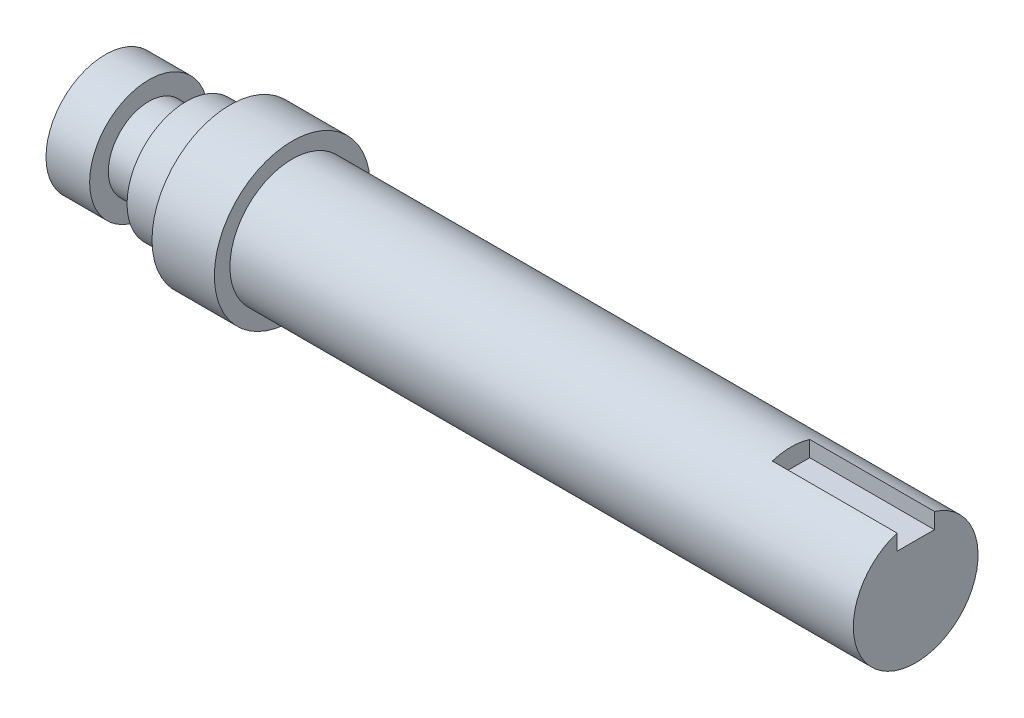
SolidWorks part; units mm, degrees
ref_plane "Front Plane" through (0, 0, 0) normal (0, 0, 1) x (1, 0, 0)
ref_plane "Top Plane" through (0, 0, 0) normal (0, 1, 0) x (1, 0, 0)
ref_plane "Right Plane" through (0, 0, 0) normal (1, 0, 0) x (0, 0, -1)
sketch "Sketch1" plane through (0, 0, 0) normal (0, 0, 1) x (1, 0, 0)
  line L0 (0, 0) -> (0, 10)
  line L1 (0, 10) -> (-100, 10)
  line L2 (-100, 10) -> (-100, 12.5)
  line L3 (-100, 12.5) -> (-110, 12.5)
  line L4 (-110, 12.5) -> (-110, 9.5)
  line L5 (-110, 9.5) -> (-130, 9.5)
  line L6 (-130, 9.5) -> (-130, 0)
  line L7 (-130, 0) -> (0, 0)
  dimension "D1" = 100
  dimension "D2" = 10
  dimension "D3" = 20
  dimension "D4" = 9.5
  dimension "D5" = 10
  dimension "D6" = 12.5
revolve "Revolve1" add sketch "Sketch1" angle 360 about L7
sketch "Sketch2" plane through (0, 0, 0) normal (0, 0, 1) x (1, 0, 0)
  line L0 (-110, 9.5) -> (-130, 9.5) construction
  line L1 (-117, 9.5) -> (-123, 9.5)
  line L2 (-117, 9.5) -> (-117, 6.5)
  line L3 (-117, 6.5) -> (-123, 6.5)
  line L4 (-123, 9.5) -> (-123, 6.5)
  line L5 (-130, 9.5) -> (-130, -9.5) construction
  line L6 (-130, 0) -> (-102.622, 0) construction
  dimension "D1" = 6
  dimension "D2" = 3
  dimension "D3" = 7
revolve "Cut-Revolve1" cut sketch "Sketch2" angle 360 about L6
sketch "Sketch3" plane through (0, 0, 0) normal (0, 0, 1) x (1, 0, 0)
  line L0 (0, 10) -> (-100, 10) construction
  line L1 (0, 12) -> (-20, 12)
  line L2 (0, 12) -> (0, 7)
  line L3 (0, 7) -> (-20, 7)
  line L4 (-20, 12) -> (-20, 7)
  line L5 (0, -10) -> (0, 10) construction
  dimension "D1" = 3
  dimension "D2" = 20
  dimension "D3" = 20
  dimension "D4" = 5
extrude "Cut-Extrude1" cut sketch "Sketch3" against normal mid plane 6
